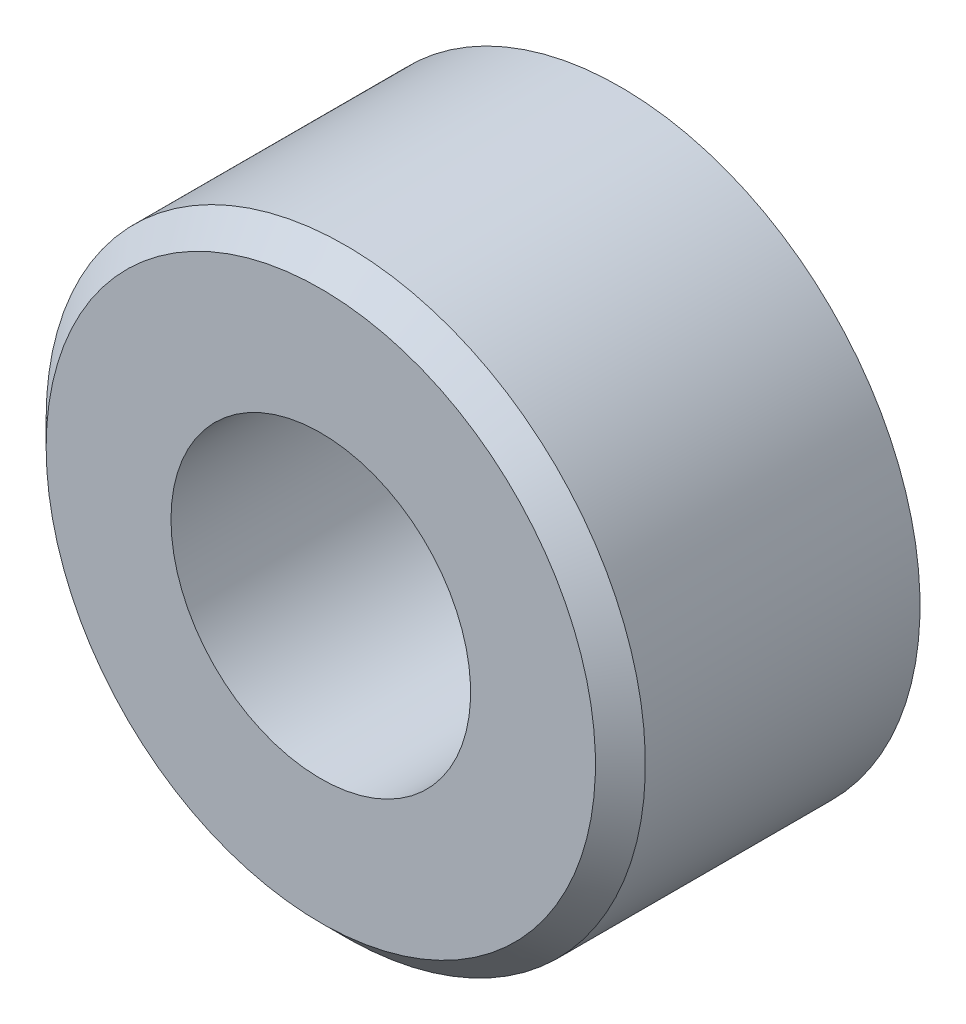
SolidWorks part; units mm, degrees
ref_plane "Front Plane" through (0, 0, 0) normal (0, 0, 1) x (1, 0, 0)
ref_plane "Top Plane" through (0, 0, 0) normal (0, 1, 0) x (1, 0, 0)
ref_plane "Right Plane" through (0, 0, 0) normal (1, 0, 0) x (0, 0, -1)
ref_plane "Plane1" through (0, 0, 0) normal (0, -1, 0) x (1, 0, 0)
sketch "Sketch1" plane through (0, 0, 0) normal (0, -1, 0) x (1, 0, 0)
  line L0 (3, 6) -> (3, 0)
  line L1 (3, 0) -> (6, 0)
  line L2 (6, 0) -> (6, 5.5)
  line L3 (6, 5.5) -> (5.5, 6)
  line L4 (5.5, 6) -> (3, 6)
  line L5 (0, 6) -> (0, 0) construction
revolve "Revolve1" add sketch "Sketch1" angle 360 about L5
